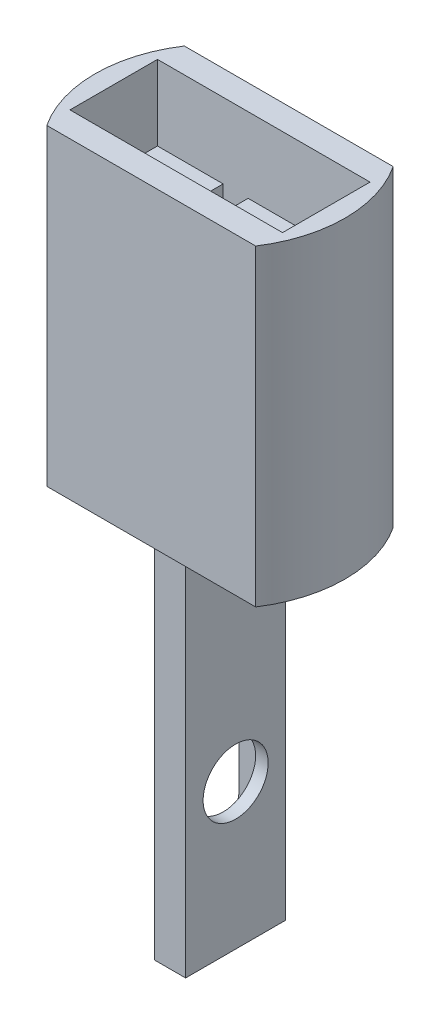
SolidWorks part; units mm, degrees
ref_plane "Front Plane" through (0, 0, 0) normal (0, 0, 1) x (1, 0, 0)
ref_plane "Top Plane" through (0, 0, 0) normal (0, 1, 0) x (1, 0, 0)
ref_plane "Right Plane" through (0, 0, 0) normal (1, 0, 0) x (0, 0, -1)
sketch "Sketch3" plane through (0, 0, 0) normal (0, 1, 0) x (1, 0, 0)
  circle A0 centre (0, 0) radius 10
  dimension "D1" = 20
extrude "Boss-Extrude1" add sketch "Sketch3" along normal blind 25
sketch "Sketch4" plane through (0, 0, 0) normal (0, -1, 0) x (-1, 0, 0)
  line L1 (1.25, 4) -> (-1.25, 4)
  line L2 (1.25, 4) -> (1.25, -4)
  line L3 (1.25, -4) -> (-1.25, -4)
  line L4 (-1.25, 4) -> (-1.25, -4)
  line L5 (1.25, 4) -> (-1.25, -4) construction
  line L6 (1.25, -4) -> (-1.25, 4) construction
  point P0 (0, 0)
  dimension "D1" = 2.5
  dimension "D2" = 8
  dimension "D3" = 0
extrude "Boss-Extrude2" add sketch "Sketch4" along normal blind 30
sketch "Sketch5" plane through (1.25, 0, 0) normal (1, 0, 0) x (0, 0, -1)
  line L1 (4, 0) -> (-4, 0) construction
  circle A0 centre (0, -18.4) radius 2.6
  dimension "D1" = 5.2
  dimension "D2" = 18.4
extrude "Cut-Extrude1" cut sketch "Sketch5" against normal up to next
sketch "Sketch7" plane through (0, 25, 0) normal (0, 1, 0) x (1, 0, 0)
  line L0 (-10, 0) -> (10, 0) construction
  line L1 (-8.5, -3.5) -> (8.5, -3.5)
  line L2 (-8.5, -3.5) -> (-8.5, 3.5)
  line L3 (-8.5, 3.5) -> (8.5, 3.5)
  line L4 (8.5, -3.5) -> (8.5, 3.5)
  circle A0 centre (0, 0) radius 10 construction
  point P4 (-8.5, 0)
  dimension "D1" = 7
  dimension "D2" = 17
  dimension "D3" = 1.5
extrude "Cut-Extrude3" cut sketch "Sketch7" against normal blind 6
sketch "Sketch8" plane through (0, 19, 0) normal (0, 1, 0) x (1, 0, 0)
  line L0 (8.5, 0) -> (-1.25, 0) construction
  line L1 (8.5, -3.5) -> (8.5, 3.5) construction
  line L2 (8.5, 3.5) -> (-8.5, 3.5) construction
  line L3 (-1.25, 3.5) -> (-3.25, 3.5)
  line L4 (-1.25, 3.5) -> (-1.25, -3.5)
  line L5 (-1.25, -3.5) -> (-3.25, -3.5)
  line L6 (-3.25, 3.5) -> (-3.25, -3.5)
  line L7 (-8.5, 3.5) -> (-8.5, -3.5) construction
  dimension "D1" = 9.75
  dimension "D2" = 2
extrude "Cut-Extrude4" cut sketch "Sketch8" against normal blind 4
sketch "Sketch11" plane through (-1.25, 0, 0) normal (-1, 0, 0) x (0, 0, 1)
  line L0 (-2.75, -7.9) -> (2.75, -28.9) construction
  line L1 (2.75, -28.9) -> (-2.75, -28.9)
  line L2 (2.75, -28.9) -> (2.75, -7.9)
  line L3 (2.75, -7.9) -> (-2.75, -7.9)
  line L4 (-2.75, -28.9) -> (-2.75, -7.9)
  line L5 (-2.75, -28.9) -> (2.75, -7.9) construction
  line L6 (-2.6, -18.4) -> (2.6, -18.4) construction
  line L7 (0, -15.8) -> (0, -21) construction
  circle A0 centre (0, -18.4) radius 2.6 construction
  point P11 (0, -18.4)
  point P12 (0, -18.4)
  dimension "D1" = 5.5
  dimension "D2" = 21
extrude "Cut-Extrude7" cut sketch "Sketch11" against normal blind 1.5
sketch "Sketch9" plane through (0, 0, 0) normal (0, -1, 0) x (1, 0, 0)
  line L0 (8.3516, -5.5) -> (-8.3516, -5.5)
  line L1 (-1.25, -4) -> (1.25, -4) construction
  line L2 (0, -5.5) -> (0, -4) construction
  line L3 (8.3516, 5.5) -> (-8.3516, 5.5)
  line L4 (0, 4) -> (0, 5.5) construction
  line L5 (1.25, 4) -> (-1.25, 4) construction
  circle A0 centre (0, 0) radius 10 construction
  arc A1 (8.3516, -5.5) -> (-8.3516, -5.5) centre (0, 0) cw
  arc A2 (-8.3516, 5.5) -> (8.3516, 5.5) centre (0, 0) cw
  dimension "D1" = 1.5
extrude "Cut-Extrude5" cut sketch "Sketch9" against normal blind 43
sketch "Sketch10" plane through (-1.25, 0, 0) normal (-1, 0, 0) x (0, 0, 1)
  line L0 (-2.75, -28.9) -> (-2.75, -21.9)
  line L1 (-2.75, -21.9) -> (-1.5, -28.9)
  line L2 (-1.5, -28.9) -> (-2.75, -28.9)
  line L3 (-2.75, -18.4) -> (2.75, -18.4) construction
  line L4 (0, -28.9) -> (0, -7.9) construction
  line L5 (1.5, -28.9) -> (2.75, -28.9)
  line L6 (2.75, -21.9) -> (1.5, -28.9)
  line L7 (2.75, -28.9) -> (2.75, -21.9)
  line L8 (2.75, -7.9) -> (2.75, -14.9)
  line L9 (2.75, -14.9) -> (1.5, -7.9)
  line L10 (1.5, -7.9) -> (2.75, -7.9)
  line L11 (-1.5, -7.9) -> (-2.75, -7.9)
  line L12 (-2.75, -14.9) -> (-1.5, -7.9)
  line L13 (-2.75, -7.9) -> (-2.75, -14.9)
  line L14 (0, -15.8) -> (0, -21) construction
  line L15 (2.6, -18.4) -> (-2.6, -18.4) construction
  line L16 (4, 0) -> (-4, 0) construction
  line L17 (-4, -30) -> (-4, 0) construction
  circle A0 centre (0, -18.4) radius 2.6 construction
  dimension "D1" = 1.25
  dimension "D2" = 2.5
  dimension "D3" = 7.9
  dimension "D4" = 14.9
extrude "Boss-Extrude3" add sketch "Sketch10" against normal blind 1.5
